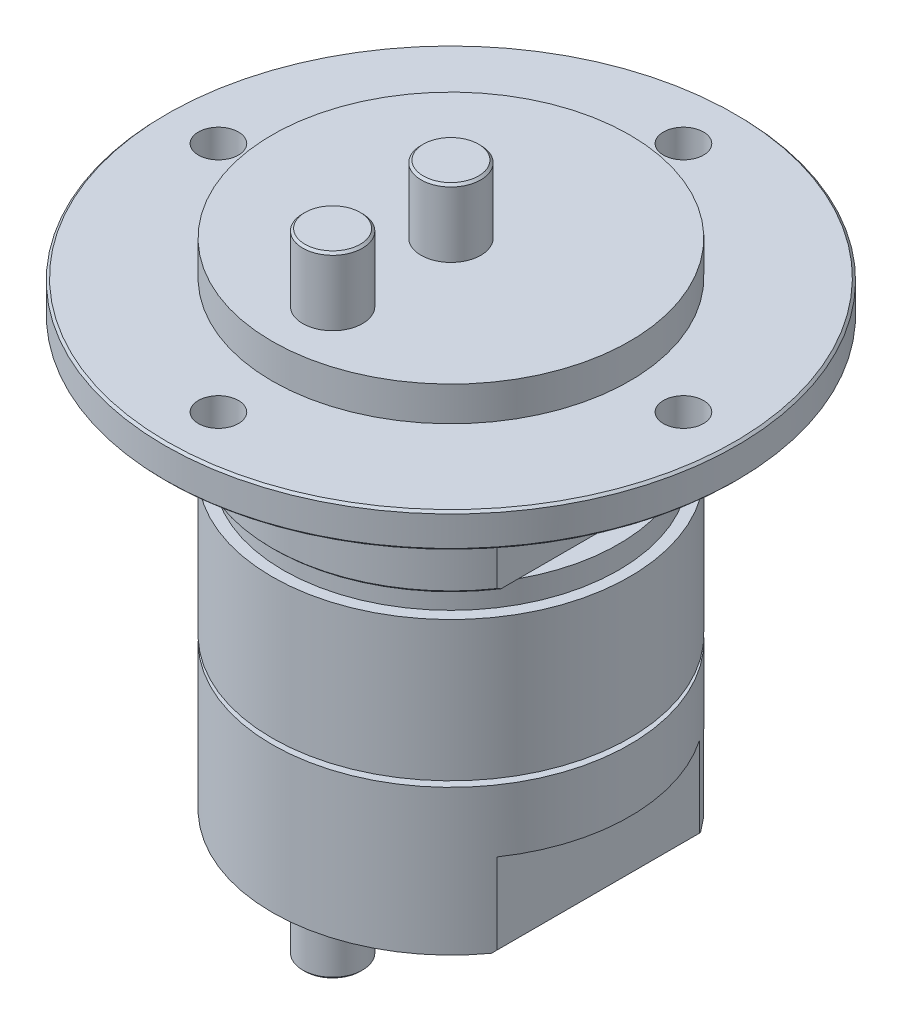
SolidWorks part; units mm, degrees
ref_plane "Front Plane" through (0, 0, 0) normal (0, 0, 1) x (1, 0, 0)
ref_plane "Top Plane" through (0, 0, 0) normal (0, 1, 0) x (1, 0, 0)
ref_plane "Right Plane" through (0, 0, 0) normal (1, 0, 0) x (0, 0, -1)
sketch "Sketch1" plane through (0, 0, 0) normal (0, 0, 1) x (1, 0, 0)
  line L0 (0, 50.7193) -> (0, -66.2106) construction
  line L1 (0, 3.05) -> (-15.875, 3.05)
  line L2 (-15.875, 3.05) -> (-15.875, 0)
  line L3 (-15.875, 0) -> (-25.4, 0)
  line L4 (-25.4, 0) -> (-25.4, -3.05)
  line L5 (-25.4, -3.05) -> (-15.875, -3.05)
  line L6 (-15.875, -3.05) -> (-15.875, -13.05)
  line L7 (-15.875, -13.05) -> (-14.875, -13.05)
  line L8 (-14.875, -13.05) -> (-14.875, -15.05)
  line L9 (-14.875, -15.05) -> (-15.875, -15.05)
  line L10 (-15.875, -15.05) -> (-15.875, -27.45)
  line L11 (-15.875, -27.45) -> (-14.875, -27.45)
  line L12 (-14.875, -27.45) -> (-14.875, -27.95)
  line L13 (-14.875, -27.95) -> (-15.875, -27.95)
  line L14 (-15.875, -27.95) -> (-15.875, -40.85)
  line L15 (-15.875, -40.85) -> (0, -40.85)
  line L16 (0, 3.05) -> (0, -40.85)
  dimension "D1" = 15.875
  dimension "D2" = 25.4
  dimension "D3" = 3.05
  dimension "D4" = 3.05
  dimension "D5" = 43.9
  dimension "D6" = 12.9
  dimension "D7" = 0.5
  dimension "D8" = 10
  dimension "D9" = 2
  dimension "D10" = 1
revolve "Revolve1" add sketch "Sketch1" angle 360 about L0
sketch "Sketch2" plane through (0, 3.05, 0) normal (0, 1, 0) x (1, 0, 0)
  circle A0 centre (0, 0) radius 2.65
  circle A1 centre (0, -10.5) radius 2.65
  dimension "D1" = 5.3
  dimension "D2" = 10.5
extrude "Boss-Extrude1" add sketch "Sketch2" along normal blind 6 and the other way blind 49.9
sketch "Sketch3" plane through (0, 0, 0) normal (0, 1, 0) x (1, 0, 0)
  circle A0 centre (0, 0) radius 20.64 construction
  circle A1 centre (0, 20.64) radius 1.78
  circle A2 centre (-20.64, 0) radius 1.78
  circle A3 centre (0, -20.64) radius 1.78
  circle A4 centre (20.64, 0) radius 1.78
  dimension "D1" = 41.28
  dimension "D2" = 3.56
extrude "Cut-Extrude1" cut sketch "Sketch3" against normal blind 6
sketch "Sketch4" plane through (0, 0, 0) normal (0, 0, 1) x (1, 0, 0)
  line L1 (-18.7918, -13.05) -> (-13.08, -13.05)
  line L2 (-18.7918, -13.05) -> (-18.7918, -5.65)
  line L3 (-18.7918, -5.65) -> (-13.08, -5.65)
  line L4 (-13.08, -13.05) -> (-13.08, -5.65)
  line L5 (-18.7918, -40.885) -> (-13.08, -40.885)
  line L6 (-18.7918, -40.885) -> (-18.7918, -33.485)
  line L7 (-18.7918, -33.485) -> (-13.08, -33.485)
  line L8 (-13.08, -40.885) -> (-13.08, -33.485)
  dimension "D1" = 7.4
  dimension "D2" = 7.4
  dimension "D3" = 13.08
extrude "Cut-Extrude2" cut sketch "Sketch4" against normal through all and the other way through all
mirror "Mirror1" about plane through (0, 0, 0) normal (1, 0, 0) of "Cut-Extrude2"
chamfer "Chamfer1" distance 0.2 angle 45 10 edges at (13.08, -40.85, 0) (-13.08, -40.85, 0) (0, -46.85, 13.15) (0, -46.85, 2.65) (0, 9.05, 13.15) (0, 9.05, 2.65) (0, -3.05, 25.4) (0, 0, 25.4) (0, -13.05, -15.875) (0, -13.05, 15.875)
